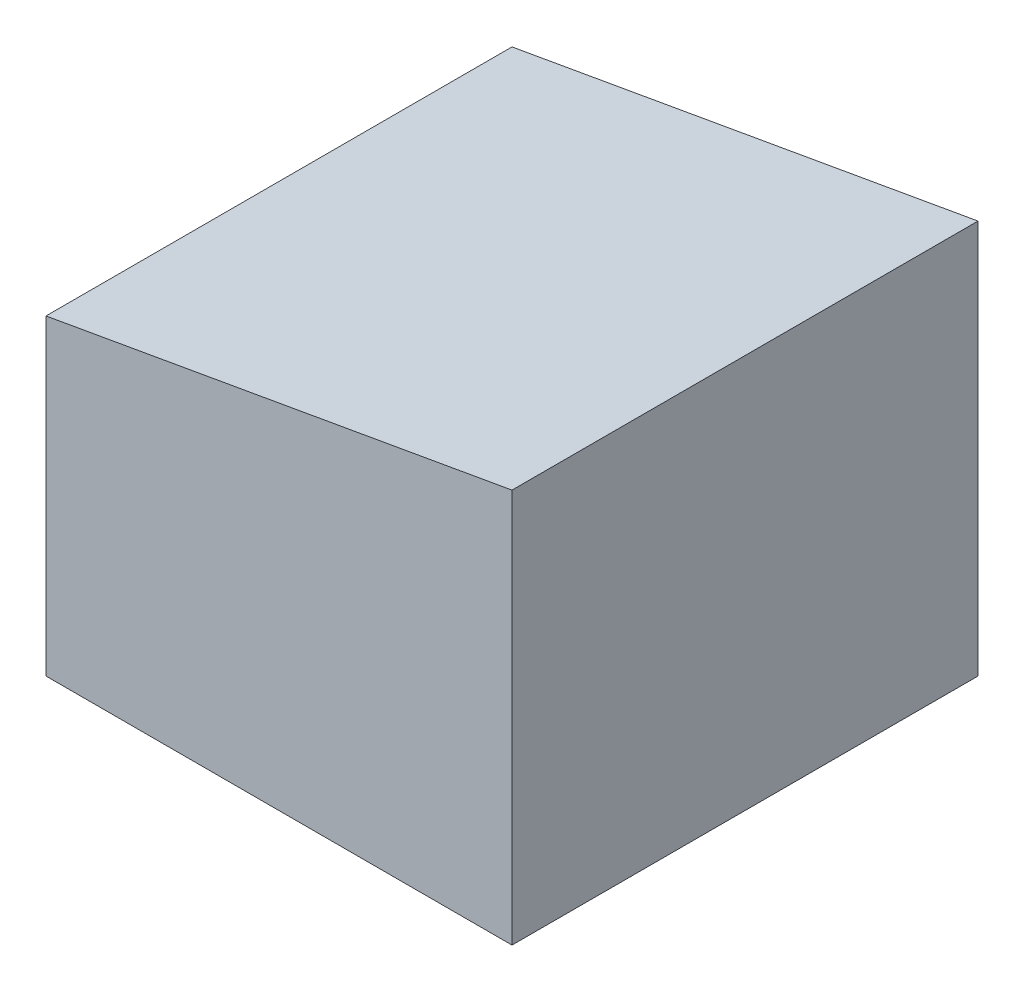
SolidWorks part; units mm, degrees
ref_plane "Front Plane" through (0, 0, 0) normal (0, 0, 1) x (1, 0, 0)
ref_plane "Top Plane" through (0, 0, 0) normal (0, 1, 0) x (1, 0, 0)
ref_plane "Right Plane" through (0, 0, 0) normal (1, 0, 0) x (0, 0, -1)
sketch "Sketch1" plane through (0, 0, 0) normal (0, 0, 1) x (1, 0, 0)
  line L0 (50.8, 42.9574) -> (0, 34)
  line L1 (0, 0) -> (50.8, 0)
  line L2 (0, 0) -> (0, 34)
  line L4 (50.8, 0) -> (50.8, 42.9574)
  dimension "D1" = 50.8
  dimension "D2" = 80
  dimension "D3" = 34
extrude "Boss-Extrude1" add sketch "Sketch1" along normal blind 50.8
